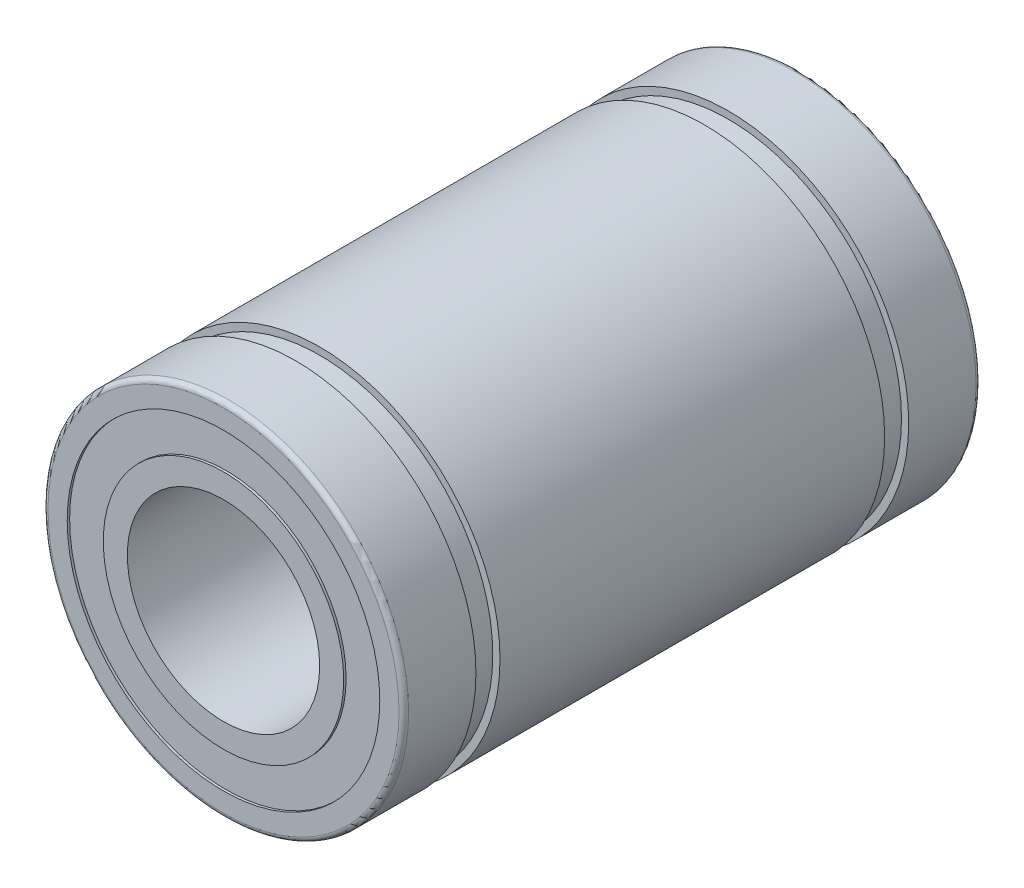
SolidWorks part; units mm, degrees
material "1023 Carbon Steel Sheet (SS)"
ref_plane "Front Plane" through (0, 0, 0) normal (0, 0, 1) x (1, 0, 0)
ref_plane "Top Plane" through (0, 0, 0) normal (0, 1, 0) x (1, 0, 0)
ref_plane "Right Plane" through (0, 0, 0) normal (1, 0, 0) x (0, 0, -1)
sketch "Sketch1" plane through (0, 0, 0) normal (1, 0, 0) x (0, 0, -1)
  line L0 (0, 7.5) -> (0, 6.5)
  line L1 (0, 6.5) -> (0.1, 6.5)
  line L2 (0.1, 6.5) -> (0.1, 5)
  line L3 (0.1, 5) -> (0, 5)
  line L4 (0, 5) -> (0, 4)
  line L5 (0, 4) -> (24, 4)
  line L6 (24, 4) -> (24, 5)
  line L7 (24, 5) -> (23.9, 5)
  line L8 (23.9, 5) -> (23.9, 6.5)
  line L9 (23.9, 6.5) -> (24, 6.5)
  line L10 (24, 6.5) -> (24, 7.5)
  line L11 (24, 7.5) -> (21, 7.5)
  line L12 (21, 7.5) -> (21, 7.2)
  line L13 (21, 7.2) -> (20, 7.2)
  line L14 (20, 7.2) -> (20, 7.5)
  line L15 (20, 7.5) -> (4, 7.5)
  line L16 (4, 7.5) -> (4, 7.2)
  line L17 (4, 7.2) -> (3, 7.2)
  line L18 (3, 7.2) -> (3, 7.5)
  line L19 (3, 7.5) -> (0, 7.5)
  line L20 (0, 0) -> (13.3897, 0) construction
  dimension "D1" = 8
  dimension "D2" = 15
  dimension "D3" = 10
  dimension "D4" = 13
  dimension "D5" = 3
  dimension "D6" = 1
  dimension "D7" = 0.3
  dimension "D8" = 24
  dimension "D9" = 0.1
revolve "Revolve1" add sketch "Sketch1" angle 360 about L20
fillet "Fillet1" radius 0.2 2 edges at (7.5, 0, -24) (7.5, 0, 0)
